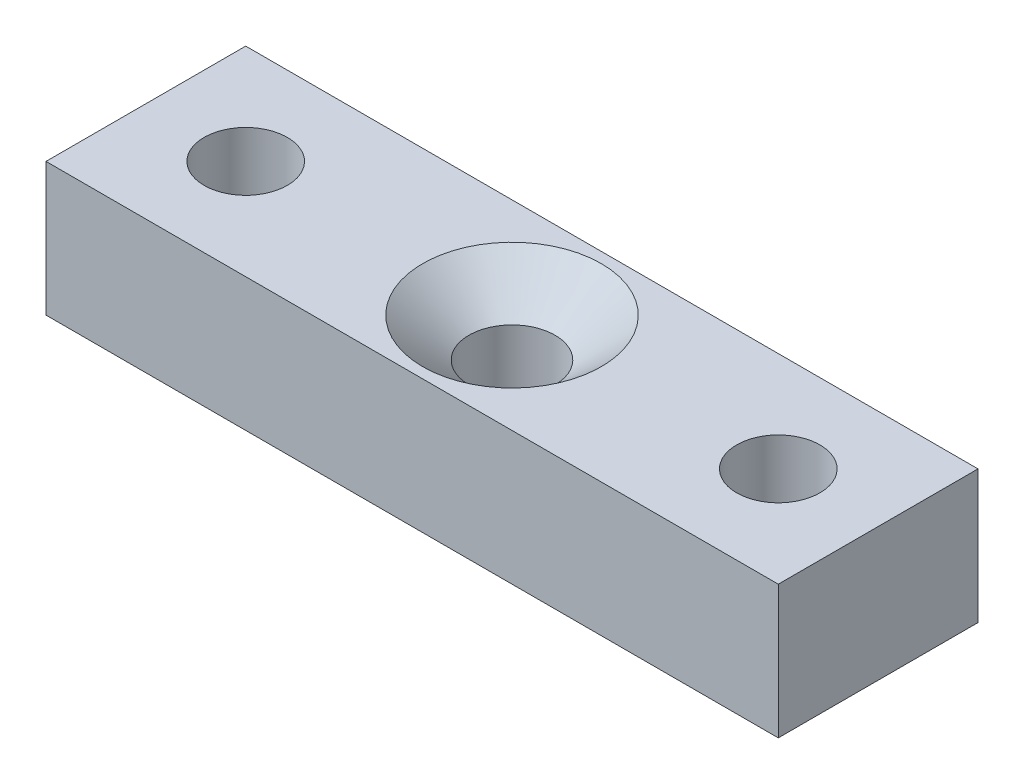
SolidWorks part; units mm, degrees
material "6061-T6 (SS)"
ref_plane "Front" through (0, 0, 0) normal (0, 0, 1) x (1, 0, 0)
ref_plane "Top" through (0, 0, 0) normal (0, 1, 0) x (1, 0, 0)
ref_plane "Right" through (0, 0, 0) normal (1, 0, 0) x (0, 0, -1)
sketch "Sketch1" plane through (0, 0, 0) normal (0, 0, 1) x (1, 0, 0)
  line L1 (-34.925, -6.35) -> (34.925, -6.35)
  line L2 (-34.925, -6.35) -> (-34.925, 6.35)
  line L3 (-34.925, 6.35) -> (34.925, 6.35)
  line L4 (34.925, -6.35) -> (34.925, 6.35)
  line L5 (-34.925, -6.35) -> (34.925, 6.35) construction
  line L6 (-34.925, 6.35) -> (34.925, -6.35) construction
  point P0 (0, 0)
  dimension "D1" = 69.85
  dimension "D2" = 12.7
extrude "Boss-Extrude1" add sketch "Sketch1" along normal blind 19.05
sketch "Sketch5" plane through (0, 6.35, 0) normal (0, 1, 0) x (1, 0, 0)
  line L0 (34.925, -9.525) -> (25.4, -9.525) construction
  line L1 (34.925, -19.05) -> (34.925, 0) construction
  line L2 (-25.4, -9.525) -> (0, -9.525) construction
  line L3 (-25.4, -9.525) -> (-34.925, -9.525) construction
  line L4 (-34.925, -19.05) -> (-34.925, 0) construction
  line L5 (0, -9.525) -> (25.4, -9.525) construction
  dimension "D1" = 50.8
hole_wizard "5/16 (0.3125) Diameter Hole1" positions "Sketch7" profile "Sketch6" hole size "5/16" standard "ANSI Inch" end condition through all
sketch "Sketch7" plane through (0, 6.35, 0) normal (0, 1, 0) x (1, 0, 0)
  point P0 (-25.4, -9.525)
  point P3 (25.4, -9.525)
sketch "Sketch6" plane through (-25.4, 6.35, 9.525) normal (1, 0, 0) x (0, 0, 1)
  line L0 (0, 0) -> (0, 12.7)
  line L1 (0, 12.7) -> (3.9687, 12.7)
  line L2 (3.9687, 12.7) -> (3.9687, 0)
  line L5 (3.9687, 0) -> (0, 0)
  line L11 (0, -6.35) -> (0, 107.95) construction
  dimension "Thru Hole Dia." = 7.9375
  dimension "Thru Hole Depth" = 12.7
hole_wizard "CSK for 5/16 Flat Head Machine Screw (100)1" positions "Sketch9" profile "Sketch8" countersink size "5/16" standard "ANSI Inch" end condition through all
sketch "Sketch9" plane through (0, 6.35, 0) normal (0, 1, 0) x (1, 0, 0)
  point P0 (0, -9.525)
sketch "Sketch8" plane through (0, 6.35, 9.525) normal (1, 0, 0) x (0, 0, 1)
  line L0 (0, 0) -> (0, 12.7)
  line L1 (0, 12.7) -> (4.1021, 12.7)
  line L2 (4.1021, 12.7) -> (4.1021, 3.7059)
  line L3 (4.1021, 3.7059) -> (8.5186, 0)
  line L5 (8.5186, 0) -> (0, 0)
  line L6 (-4.1021, 3.7059) -> (-8.5186, 0) construction
  line L11 (0, -6.35) -> (0, 107.95) construction
  dimension "Thru Hole Dia." = 8.2042
  dimension "Thru Hole Depth" = 12.7
  dimension "Near C'Sink Dia." = 17.0371
  dimension "Near C'Sink Angle" = 100
